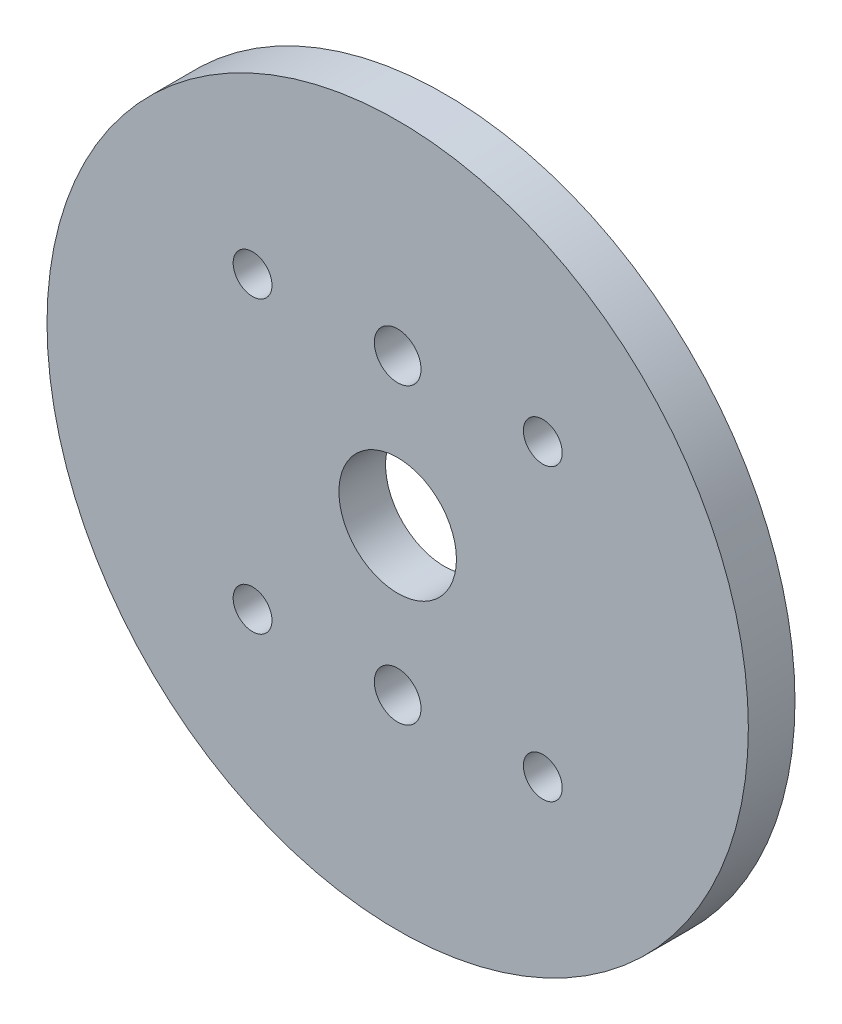
SolidWorks part; units mm, degrees
ref_plane "Front Plane" through (0, 0, 0) normal (0, 0, 1) x (1, 0, 0)
ref_plane "Top Plane" through (0, 0, 0) normal (0, 1, 0) x (1, 0, 0)
ref_plane "Right Plane" through (0, 0, 0) normal (1, 0, 0) x (0, 0, -1)
sketch "Sketch1" plane through (0, 0, 0) normal (0, 0, 1) x (1, 0, 0)
  circle A0 centre (0, 10) radius 1.5875
  circle A1 centre (0, 0) radius 23.87
  circle A2 centre (9.8783, -9.8783) radius 1.3208
  circle A3 centre (9.8783, 9.8783) radius 1.3208
  circle A4 centre (-9.8783, -9.8783) radius 1.3208
  circle A5 centre (-9.8783, 9.8783) radius 1.3208
  circle A6 centre (0, 0) radius 4
  circle A8 centre (0, -10) radius 1.5875
  dimension "D2" = 4
extrude "Boss-Extrude2" add sketch "Sketch1" along normal blind 3.175
